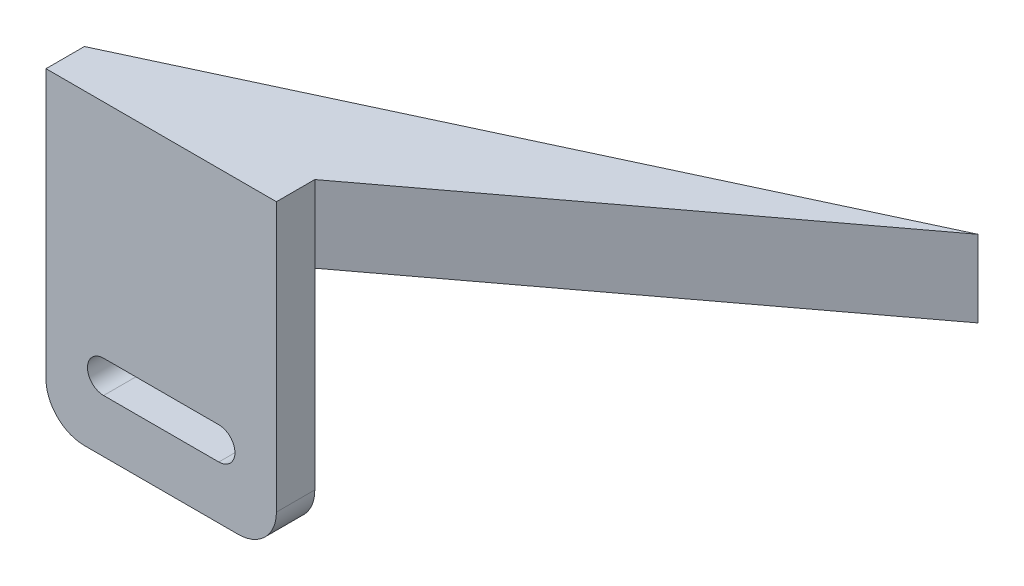
SolidWorks part; units mm, degrees
ref_plane "Front Plane" through (0, 0, 0) normal (0, 0, 1) x (1, 0, 0)
ref_plane "Top Plane" through (0, 0, 0) normal (0, 1, 0) x (1, 0, 0)
ref_plane "Right Plane" through (0, 0, 0) normal (1, 0, 0) x (0, 0, -1)
sketch "Sketch1" plane through (0, 0, 0) normal (0, 0, 1) x (1, 0, 0)
  line L1 (-15, -20) -> (15, -20)
  line L2 (-15, -20) -> (-15, 20)
  line L3 (-15, 20) -> (15, 20)
  line L4 (15, -20) -> (15, 20)
  line L5 (-15, -20) -> (15, 20) construction
  line L6 (-15, 20) -> (15, -20) construction
  point P0 (0, 0)
  dimension "D1" = 40
  dimension "D2" = 30
extrude "Boss-Extrude1" add sketch "Sketch1" along normal blind 5
sketch "Sketch2" plane through (0, 20, 0) normal (0, 1, 0) x (1, 0, 0)
  line L0 (-15, 0) -> (64.3468, 37)
  line L1 (64.3468, 37) -> (15, 0)
  line L2 (15, 0) -> (-15, 0)
  point P3 (38.249, 37.2335)
  dimension "D1" = 37
  dimension "D2" = 25
extrude "Boss-Extrude2" add sketch "Sketch2" against normal blind 10
fillet "Fillet2" radius 5 2 edges at (-15, -20, 2.5) (15, -20, 2.5)
sketch "Sketch4" plane through (0, 0, 5) normal (0, 0, 1) x (1, 0, 0)
  line L0 (0, 0) -> (0, -20) construction
  line L1 (-10, -20) -> (10, -20) construction
  line L2 (7.5, -11) -> (-7.5, -11) construction
  line L3 (7.5, -13.1) -> (-7.5, -13.1)
  line L4 (7.5, -8.9) -> (-7.5, -8.9)
  arc A0 (7.5, -13.1) -> (7.5, -8.9) centre (7.5, -11) ccw
  arc A1 (-7.5, -8.9) -> (-7.5, -13.1) centre (-7.5, -11) ccw
  point P7 (0, -11)
  dimension "D1" = 15
  dimension "D2" = 4.2
  dimension "D3" = 11
extrude "Cut-Extrude1" cut sketch "Sketch4" against normal blind 10
